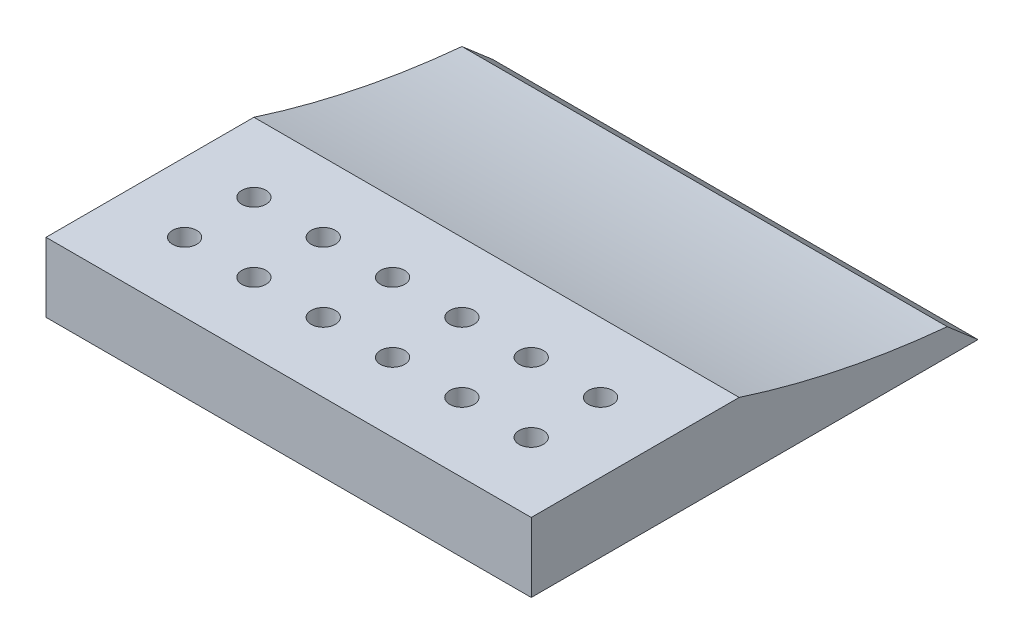
SolidWorks part; units mm, degrees
ref_plane "Front Plane" through (0, 0, 0) normal (0, 0, 1) x (1, 0, 0)
ref_plane "Top Plane" through (0, 0, 0) normal (0, 1, 0) x (1, 0, 0)
ref_plane "Right Plane" through (0, 0, 0) normal (1, 0, 0) x (0, 0, -1)
sketch "Sketch2" plane through (0, 0, 0) normal (1, 0, 0) x (0, 0, -1)
  line L1 (0, 0) -> (60, 0)
  line L2 (0, 0) -> (0, 10)
  line L3 (0, 10) -> (60, 10)
  line L4 (60, 0) -> (60, 10)
  dimension "D1" = 10
  dimension "D2" = 60
extrude "Boss-Extrude1" add sketch "Sketch2" along normal blind 70
sketch "Sketch3" plane through (70, 0, 0) normal (1, 0, 0) x (0, 0, -1)
  line L0 (-70, 76.0749) -> (-70, 118.2801) construction
  line L1 (60, 10) -> (0, 10) construction
  line L3 (0, 10) -> (0, 0) construction
  circle A0 centre (73, 143.23) radius 140
  point P8 (0, 5)
  dimension "D1" = 280
  dimension "D2" = 143
  dimension "D3" = 133.23
  dimension "D4" = 70
extrude "Cut-Extrude1" cut sketch "Sketch3" against normal blind 70
sketch "Sketch5" plane through (70, 0, 0) normal (1, 0, 0) x (0, 0, -1)
  line L0 (60, 0) -> (60, 3.8349) construction
  line L1 (60, 0) -> (60, 3.8349)
  line L2 (60, 0) -> (64.4409, 0)
  line L3 (64.4409, 0) -> (60, 3.8349)
extrude "Boss-Extrude2" add sketch "Sketch5" against normal blind 70
sketch "Sketch6" plane through (0, 10, 0) normal (0, 1, 0) x (1, 0, 0)
  line L0 (70, 29.9911) -> (0, 29.9911) construction
  line L1 (70, 29.9911) -> (70, 0) construction
  circle A0 centre (60, 19.9911) radius 1.75
  circle A1 centre (50, 19.9911) radius 1.75
  circle A2 centre (40, 19.9911) radius 1.75
  circle A3 centre (30, 19.9911) radius 1.75
  circle A4 centre (20, 19.9911) radius 1.75
  circle A5 centre (10, 19.9911) radius 1.75
  circle A6 centre (10, 9.9911) radius 1.75
  circle A7 centre (20, 9.9911) radius 1.75
  circle A8 centre (30, 9.9911) radius 1.75
  circle A9 centre (40, 9.9911) radius 1.75
  circle A10 centre (50, 9.9911) radius 1.75
  circle A11 centre (60, 9.9911) radius 1.75
  dimension "D1" = 3.5
  dimension "D2" = 10
  dimension "D3" = 10
  dimension "D4" = 6
  dimension "D5" = 2
extrude "Cut-Extrude2" cut sketch "Sketch6" against normal up to next
sketch "Sketch8" plane through (0, 0, 0) normal (0, -1, 0) x (1, 0, 0)
  circle A0 centre (10, -9.9911) radius 3
  circle A1 centre (20, -9.9911) radius 3
  circle A2 centre (30, -9.9911) radius 3
  circle A3 centre (40, -9.9911) radius 3
  circle A4 centre (50, -9.9911) radius 3
  circle A5 centre (60, -9.9911) radius 3
  circle A6 centre (20, -19.9911) radius 3
  circle A7 centre (30, -19.9911) radius 3
  circle A8 centre (40, -19.9911) radius 3
  circle A9 centre (50, -19.9911) radius 3
  circle A10 centre (60, -19.9911) radius 3
  circle A11 centre (10, -19.9911) radius 3
  dimension "D1" = 6
  dimension "D2" = 6
  dimension "D3" = 2
extrude "Cut-Extrude3" cut sketch "Sketch8" against normal blind 3
